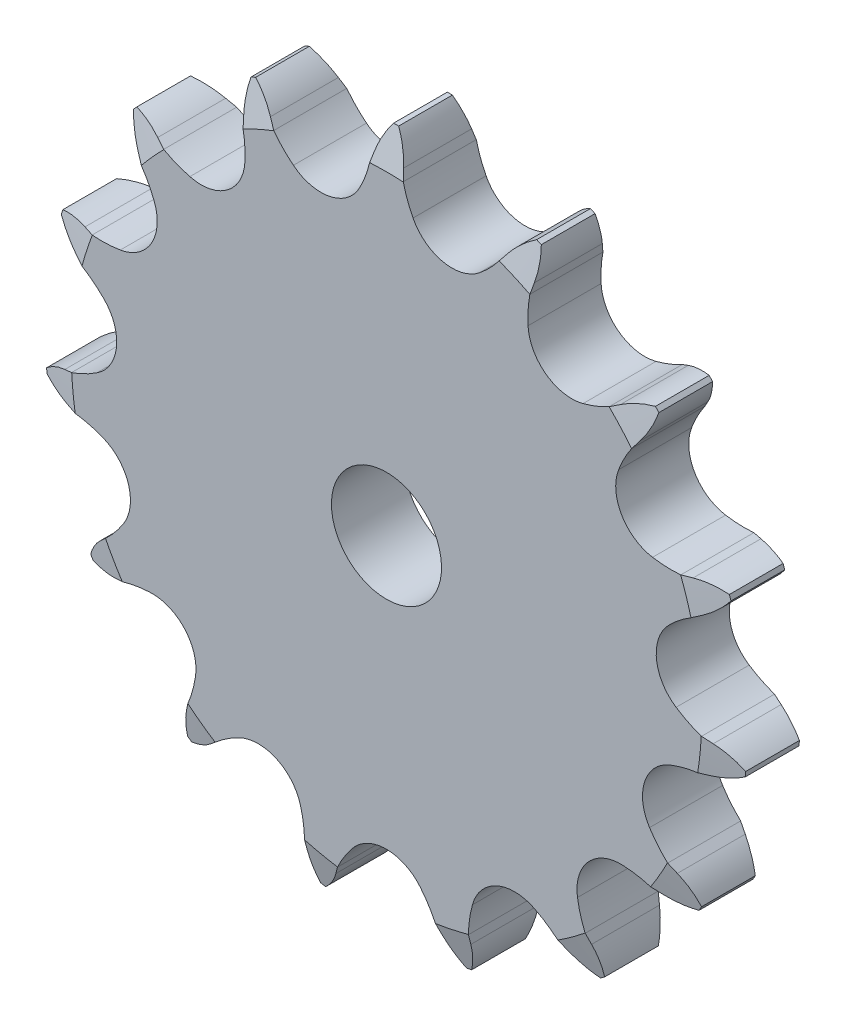
SolidWorks part; units mm, degrees
ref_plane "Front Plane" through (0, 0, 0) normal (0, 0, 1) x (1, 0, 0)
ref_plane "Top Plane" through (0, 0, 0) normal (0, 1, 0) x (1, 0, 0)
ref_plane "Right Plane" through (0, 0, 0) normal (1, 0, 0) x (0, 0, -1)
sketch "Sketch1" plane through (0, 0, 0) normal (0, 0, 1) x (1, 0, 0)
  line L3 (0, 0) -> (0, 4.5813) construction
  line L4 (-2.2906, 22.9064) -> (2.2906, 22.9064) construction
  line L5 (3.9479, 4.5813) -> (3.9479, 0) construction
  line L6 (-2.2906, 26.1033) -> (2.2906, 26.1033) construction
  line L7 (3.9479, 26.1033) -> (0.3876, 23.2202) construction
  line L8 (3.9479, 26.1033) -> (-3.5656, 22.6422) construction
  line L9 (-3.5656, 22.6422) -> (-5.4824, 26.8032) construction
  line L10 (-8.6957, 4.5813) -> (-8.6957, 0) construction
  line L11 (-2.2906, 21.058) -> (2.2906, 21.058) construction
  line L12 (0, 0) -> (-0.9525, 4.4812) construction
  line L13 (-3.5656, 22.6422) -> (-3.8617, 23.2849) construction
  line L14 (3.5656, 22.6422) -> (3.8617, 23.2849) construction
  line L59 (0, 0) -> (0, -15) construction
  line L60 (-5, -25.527) -> (5, -25.527) construction
  circle A0 centre (0, 0) radius 4 construction
  circle A2 centre (0, 0) radius 25.527 construction
  circle A8 centre (0, 0) radius 22.9064 construction
  circle A9 centre (0, 22.9064) radius 3.1781 construction
  arc A10 (-3.5656, 22.6422) -> (-2.4698, 20.9063) centre (3.9234, 26.1559) ccw construction
  circle A11 centre (-8.6957, 21.058) radius 5.3223 construction
  arc A12 (2.4698, 20.9063) -> (-2.4698, 20.9063) centre (0, 22.9064) cw construction
  arc A13 (-2.4698, 20.9063) -> (-3.5656, 22.6422) centre (3.9234, 26.1559) cw construction
  arc A14 (-3.8617, 23.2849) -> (-5.357, 25.2029) centre (-8.6957, 21.058) ccw construction
  arc A15 (2.4698, 20.9063) -> (3.5656, 22.6422) centre (-3.9234, 26.1559) ccw construction
  arc A16 (3.8617, 23.2849) -> (5.357, 25.2029) centre (8.6957, 21.058) cw construction
  arc A127 (-5.357, 25.2029) -> (5.357, 25.2029) centre (0, 22.9064) cw construction
  point P3 (0, 22.9064)
  point P7 (0, 21.058)
  point P11 (0, -25.527)
  point P24 (3.9479, 26.1033)
  point P27 (0, 22.9064)
  point P38 (-5.357, 25.2029)
  point P50 (0, 26.1033)
  dimension "For Shaft Diameter" = 8
  dimension "No. of Teeth" = 15
  dimension "D3" = 4.5813
  dimension "Pitch" = 10
sketch "Sketch2" plane through (0, 0, 0) normal (1, 0, 0) x (0, 0, -1)
  line L1 (-2.655, 4) -> (2.655, 4) construction
  line L3 (-2.655, -25.527) -> (2.655, -25.527) construction
  line L4 (-2.655, 25.527) -> (2.655, 25.527) construction
  line L11 (-2.655, 0) -> (2.655, 0) construction
  point P4 (0, 4)
  point P6 (0, 25.527)
  point P10 (0, -25.527)
  point P14 (0, 0)
  dimension "O'all Width" = 5.31
sketch "Sketch3" plane through (0, 0, 0) normal (1, 0, 0) x (0, 0, -1)
  line L0 (-2.655, 25.527) -> (2.655, 25.527) construction
  line L1 (-2.655, 4) -> (2.655, 4)
  line L2 (-2.655, 4) -> (-2.655, 25.527)
  line L3 (-2.655, 25.527) -> (2.655, 25.527)
  line L4 (2.655, 4) -> (2.655, 25.527)
  line L5 (-2.655, 4) -> (2.655, 4) construction
revolve "Revolve5" add sketch "Sketch3" angle 360 about L11
sketch "Sketch4" plane through (0, 0, 0) normal (0, 0, 1) x (1, 0, 0)
  line L0 (-3.5656, 22.6422) -> (-3.8617, 23.2849) construction
  line L1 (1.2199, 22.8887) -> (1.0639, 23.5789)
  line L2 (-3.5656, 22.6422) -> (-3.8617, 23.2849) construction
  line L4 (3.5656, 22.6422) -> (3.8617, 23.2849) construction
  line L5 (3.5656, 22.6422) -> (3.8617, 23.2849) construction
  line L6 (0, 0) -> (0, 25.527) construction
  line L9 (8.1953, 21.4061) -> (8.6185, 21.9731)
  line L10 (0, 0) -> (4.7625, 22.4058) construction
  line L11 (0, 0) -> (-4.7625, 22.4058) construction
  arc A0 (-3.8617, 23.2849) -> (-5.357, 25.2029) centre (-8.6957, 21.058) ccw construction
  arc A1 (-3.5656, 22.6422) -> (-2.4698, 20.9063) centre (3.9234, 26.1559) ccw construction
  arc A2 (-2.4698, 20.9063) -> (2.4698, 20.9063) centre (0, 22.9064) ccw construction
  circle A3 centre (0, 0) radius 25.527 construction
  arc A6 (-3.8617, 23.2849) -> (-5.357, 25.2029) centre (-8.6957, 21.058) ccw construction
  arc A7 (-3.5656, 22.6422) -> (-2.4698, 20.9063) centre (3.9234, 26.1559) ccw construction
  arc A8 (-2.4698, 20.9063) -> (2.4698, 20.9063) centre (0, 22.9064) ccw construction
  arc A12 (2.4698, 20.9063) -> (3.5656, 22.6422) centre (-3.9234, 26.1559) ccw construction
  arc A13 (5.357, 25.2029) -> (3.8617, 23.2849) centre (8.6957, 21.058) ccw construction
  arc A14 (5.357, 25.2029) -> (-5.357, 25.2029) centre (0, 22.9064) ccw construction
  arc A15 (2.4698, 20.9063) -> (3.5656, 22.6422) centre (-3.9234, 26.1559) ccw construction
  arc A16 (5.357, 25.2029) -> (3.8617, 23.2849) centre (8.6957, 21.058) ccw construction
  arc A17 (5.357, 25.2029) -> (-5.357, 25.2029) centre (0, 22.9064) ccw construction
  arc A23 (10.48, 23.5384) -> (0, 25.766) centre (4.7625, 22.4058) ccw
  arc A24 (1.0639, 23.5789) -> (0, 25.766) centre (-4.1275, 22.4058) ccw
  arc A25 (1.2199, 22.8887) -> (1.9308, 20.963) centre (9.2758, 24.7686) ccw
  arc A26 (1.9308, 20.963) -> (6.7625, 19.936) centre (4.7625, 22.4058) ccw
  arc A27 (6.7625, 19.936) -> (8.1953, 21.4061) centre (1.6004, 26.4001) ccw
  arc A28 (10.48, 23.5384) -> (8.6185, 21.9731) centre (12.8839, 18.7899) ccw
  circle A29 centre (0, 0) radius 22.9064 construction
  circle A30 centre (0, 0) radius 17.0778 construction
  dimension "D2" = 12
  dimension "D1" = 12
  dimension "D5" = 24.733
  dimension "D3" = 2
extrude "Cut-Extrude4" cut sketch "Sketch4" against normal through all both and the other way through all
pattern_circular "CirPattern2" count 15 over 360 about axis through (0, 0, 0) along (0, 0, 1) of "Cut-Extrude4"
sketch "Sketch5" plane through (0, 0, 2.655) normal (0, 0, 1) x (1, 0, 0)
  circle A0 centre (0, 0) radius 22.9064 construction
  circle A1 centre (0, 0) radius 22.9064
extrude "Cut-Extrude5" cut sketch "Sketch5" against normal through all draft 75 flip side to cut
sketch "Sketch6" plane through (0, 0, -2.655) normal (0, 0, -1) x (-1, 0, 0)
  circle A1 centre (0, 0) radius 22.9064
  circle A2 centre (0, 0) radius 22.9064
  dimension "D1" = 0
extrude "Cut-Extrude6" cut sketch "Sketch6" against normal through all draft 75 flip side to cut
sketch "Sketch7" plane through (0, 0, 0) normal (0, 0, 1) x (1, 0, 0)
  point P0 (4.7625, 22.4058)
  point P1 (-4.7625, 22.4058)
equation "\"D1@Sketch1\"=\"E@Sketch1\""
equation "\"No. of Teeth@CirPattern2\"=\"No. of Teeth@Sketch1\""
equation "\"D2@Sketch4\" =  ( 360 / \"No. of Teeth@Sketch1\" )  * .5"
equation "\"D1@Sketch4\" = \"D2@Sketch4\""
equation "\"D5@Sketch4\"=\"D4@Sketch4\""
equation "\"D3@Sketch1\"=\"PD@Sketch1\"*.1"
